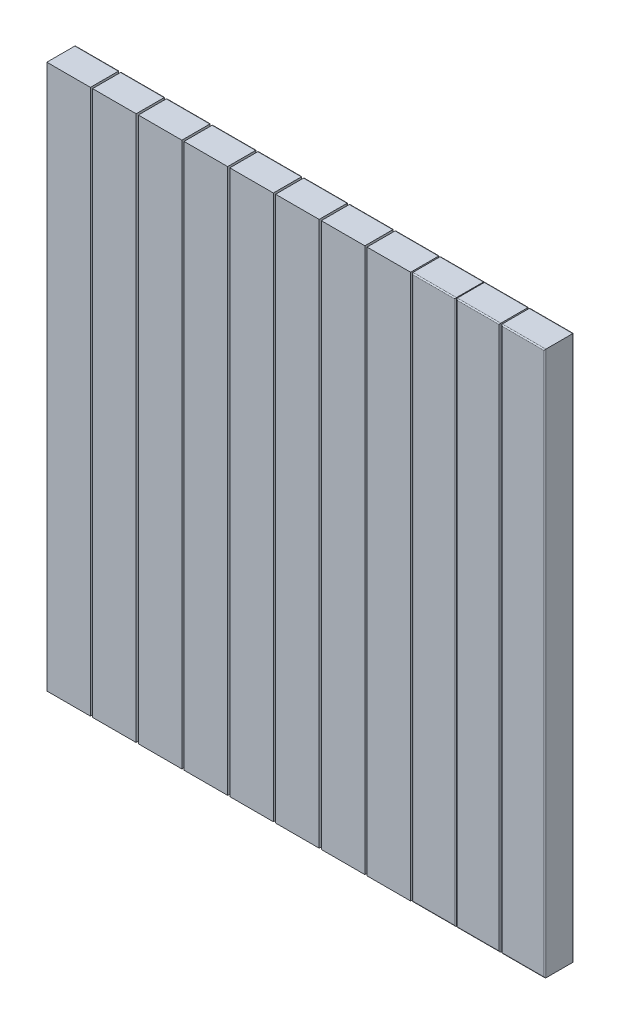
SolidWorks part; units mm, degrees
ref_plane "Front Plane" through (0, 0, 0) normal (0, 0, 1) x (1, 0, 0)
ref_plane "Top Plane" through (0, 0, 0) normal (0, 1, 0) x (1, 0, 0)
ref_plane "Right Plane" through (0, 0, 0) normal (1, 0, 0) x (0, 0, -1)
sketch "Sketch1" plane through (0, 0, 0) normal (0, 0, 1) x (1, 0, 0)
  line L0 (210, 0) -> (210, 2500)
  line L1 (0, 0) -> (200, 0)
  line L2 (0, 0) -> (0, 2500)
  line L3 (0, 2500) -> (200, 2500)
  line L4 (200, 0) -> (200, 2500)
  line L5 (210, 2500) -> (410, 2500)
  line L6 (410, 0) -> (410, 2500)
  line L7 (210, 0) -> (410, 0)
  line L8 (420, 0) -> (420, 2500)
  line L9 (420, 2500) -> (620, 2500)
  line L10 (620, 0) -> (620, 2500)
  line L11 (420, 0) -> (620, 0)
  line L12 (630, 0) -> (630, 2500)
  line L13 (630, 2500) -> (830, 2500)
  line L14 (830, 0) -> (830, 2500)
  line L15 (630, 0) -> (830, 0)
  line L16 (840, 0) -> (840, 2500)
  line L17 (840, 2500) -> (1040, 2500)
  line L18 (1040, 0) -> (1040, 2500)
  line L19 (840, 0) -> (1040, 0)
  line L20 (1050, 0) -> (1050, 2500)
  line L21 (1050, 2500) -> (1250, 2500)
  line L22 (1250, 0) -> (1250, 2500)
  line L23 (1050, 0) -> (1250, 0)
  line L24 (1260, 0) -> (1260, 2500)
  line L25 (1260, 2500) -> (1460, 2500)
  line L26 (1460, 0) -> (1460, 2500)
  line L27 (1260, 0) -> (1460, 0)
  line L28 (1470, 0) -> (1470, 2500)
  line L29 (1470, 2500) -> (1670, 2500)
  line L30 (1670, 0) -> (1670, 2500)
  line L31 (1470, 0) -> (1670, 0)
  line L32 (1875.9972, 0) -> (1875.9972, 2500)
  line L33 (1675.9972, 0) -> (1675.9972, 2500)
  line L34 (1675.9972, 0) -> (1875.9972, 0)
  line L35 (1675.9972, 2500) -> (1875.9972, 2500)
  line L36 (2079.782, 0) -> (2079.782, 2500)
  line L37 (1879.782, 0) -> (1879.782, 2500)
  line L38 (1879.782, 0) -> (2079.782, 0)
  line L39 (1879.782, 2500) -> (2079.782, 2500)
  line L40 (2286.1467, 0) -> (2286.1467, 2500)
  line L41 (2086.1467, 0) -> (2086.1467, 2500)
  line L42 (2086.1467, 0) -> (2286.1467, 0)
  line L43 (2086.1467, 2500) -> (2286.1467, 2500)
  dimension "D1" = 2500
  dimension "D2" = 200
  dimension "D3" = 8
extrude "Boss-Extrude1" add sketch "Sketch1" along normal blind 133
fillet "Fillet1" radius 5 4 edges at (100, 0, 0) (200, 1250, 0) (100, 2500, 0) (0, 1250, 0)
fillet "Fillet2" radius 5 4 edges at (1670, 1250, 0) (1570, 2500, 0) (1470, 1250, 0) (1570, 0, 0)
fillet "Fillet3" radius 5 4 edges at (1460, 1250, 0) (1360, 2500, 0) (1260, 1250, 0) (1360, 0, 0)
fillet "Fillet4" radius 5 4 edges at (1250, 1250, 0) (1150, 2500, 0) (1050, 1250, 0) (1150, 0, 0)
fillet "Fillet5" radius 5 4 edges at (1040, 1250, 0) (940, 2500, 0) (840, 1250, 0) (940, 0, 0)
fillet "Fillet6" radius 5 4 edges at (830, 1250, 0) (730, 2500, 0) (630, 1250, 0) (730, 0, 0)
fillet "Fillet7" radius 5 4 edges at (620, 1250, 0) (520, 2500, 0) (420, 1250, 0) (520, 0, 0)
fillet "Fillet8" radius 5 4 edges at (410, 1250, 0) (310, 2500, 0) (210, 1250, 0) (310, 0, 0)
fillet "Fillet9" radius 5 4 edges at (1675.9972, 1250, 133) (1775.9972, 2500, 133) (1875.9972, 1250, 133) (1775.9972, 0, 133)
fillet "Fillet10" radius 5 4 edges at (1879.782, 1250, 133) (1979.782, 2500, 133) (2079.782, 1250, 133) (1979.782, 0, 133)
fillet "Fillet11" radius 5 4 edges at (2086.1467, 1250, 133) (2186.1467, 2500, 133) (2286.1467, 1250, 133) (2186.1467, 0, 133)
fillet "Fillet12" radius 5 4 edges at (2079.782, 1250, 0) (1979.782, 2500, 0) (1879.782, 1250, 0) (1979.782, 0, 0)
fillet "Fillet13" radius 5 4 edges at (1875.9972, 1250, 0) (1775.9972, 2500, 0) (1675.9972, 1250, 0) (1775.9972, 0, 0)
fillet "Fillet14" radius 5 4 edges at (2286.1467, 1250, 0) (2186.1467, 2500, 0) (2086.1467, 1250, 0) (2186.1467, 0, 0)
